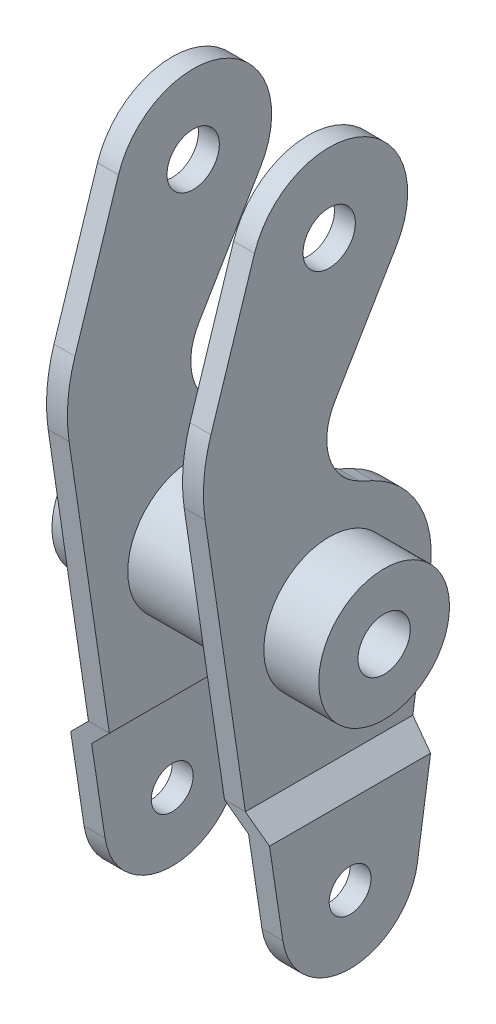
SolidWorks part; units mm, degrees
ref_plane "Спереди" through (0, 0, 0) normal (0, 0, 1) x (1, 0, 0)
ref_plane "Сверху" through (0, 0, 0) normal (0, 1, 0) x (1, 0, 0)
ref_plane "Справа" through (0, 0, 0) normal (1, 0, 0) x (0, 0, -1)
sketch "Эскиз1" plane through (0, 0, 0) normal (1, 0, 0) x (0, 0, -1)
  circle A0 centre (0, 0) radius 12.5
  circle A1 centre (0, 0) radius 5
  dimension "D1" = 25
  dimension "D2" = 10
extrude "Бобышка-Вытянуть1" add sketch "Эскиз1" along normal mid plane 51
ref_plane "Плоскость1" through (11, 0, 0) normal (1, 0, 0) x (0, 0, -1)
sketch "Эскиз2" plane through (11, 0, 0) normal (1, 0, 0) x (0, 0, -1)
  line L0 (0, 124.0102) -> (0, -101.716) construction
  line L1 (19.286, -2.8807) -> (12.8574, -45.9205)
  line L3 (-16.0178, -25) -> (-12.8541, -45.9419)
  line L4 (-16.0178, -25) -> (-23.7221, 27.1424)
  line L5 (-22.6035, 40.7132) -> (-14.2796, 66.5929)
  line L7 (1.0793, 34.4058) -> (12.9031, 54.3508)
  line L8 (5.7097, 18.9144) -> (8.5655, 17.518)
  circle A0 centre (0, 0) radius 5
  circle A1 centre (0, -44) radius 4
  circle A2 centre (0, 62) radius 5
  arc A3 (-12.8541, -45.9419) -> (12.8574, -45.9205) centre (0, -44) ccw
  arc A4 (12.9031, 54.3508) -> (-14.2796, 66.5929) centre (0, 62) ccw
  arc A5 (-23.7221, 27.1424) -> (-22.6035, 40.7132) centre (5.9556, 31.5275) cw
  arc A6 (5.7097, 18.9144) -> (1.0793, 34.4058) centre (10.5415, 28.7964) cw
  arc A7 (19.286, -2.8807) -> (8.5655, 17.518) centre (0, 0) ccw
  point P10 (0, 67)
  point P27 (-24.744, 34.0581)
  dimension "D2" = 8
  dimension "D3" = 10
  dimension "D6" = 26
  dimension "D7" = 30
  dimension "D8" = 30
  dimension "D11" = 11
  dimension "D4" = 44
  dimension "D5" = 106
  dimension "D10" = 80
extrude "Бобышка-Вытянуть2" add sketch "Эскиз2" along normal blind 4
sketch "Эскиз3" plane through (15, 0, 0) normal (1, 0, 0) x (0, 0, -1)
  line L0 (-16.0178, -25) -> (15.9822, -25)
  line L1 (-23.7221, 27.1424) -> (-16.0178, -25) construction
  line L2 (-16.0178, -25) -> (-12.8541, -45.9419)
  line L3 (15.9822, -25) -> (12.8574, -45.9205)
  circle A0 centre (0, -44) radius 4
  arc A1 (-12.8541, -45.9419) -> (12.8574, -45.9205) centre (0, -44) ccw
  point P4 (0, -57)
  dimension "D1" = 32
  dimension "D2" = 32
extrude "Бобышка-Вытянуть3" add sketch "Эскиз3" along normal blind 4
ref_plane "Плоскость2" through (0, 0, 20) normal (0, 0, 1) x (1, 0, 0)
sketch "Эскиз5" plane through (0, 0, 20) normal (0, 0, 1) x (1, 0, 0)
  line L0 (15, -25) -> (19, -25)
  line L1 (15, -25) -> (19, -29)
  line L2 (19, -25) -> (19, -45.9419) construction
  line L3 (19, -29) -> (19, -25)
  line L4 (15, -57) -> (15, -29)
  line L5 (11, -57) -> (19, -57) construction
  line L6 (15, -29) -> (11, -25)
  line L7 (11, -41.3013) -> (11, 41.3013) construction
  line L8 (11, -25) -> (11, -57)
  line L9 (11, -57) -> (15, -57)
extrude "Вырез-Вытянуть1" cut sketch "Эскиз5" against normal blind 40
mirror "Зеркальное отражение1" about plane through (0, 0, 0) normal (1, 0, 0) of "Вырез-Вытянуть1", "Бобышка-Вытянуть2", "Бобышка-Вытянуть3"
